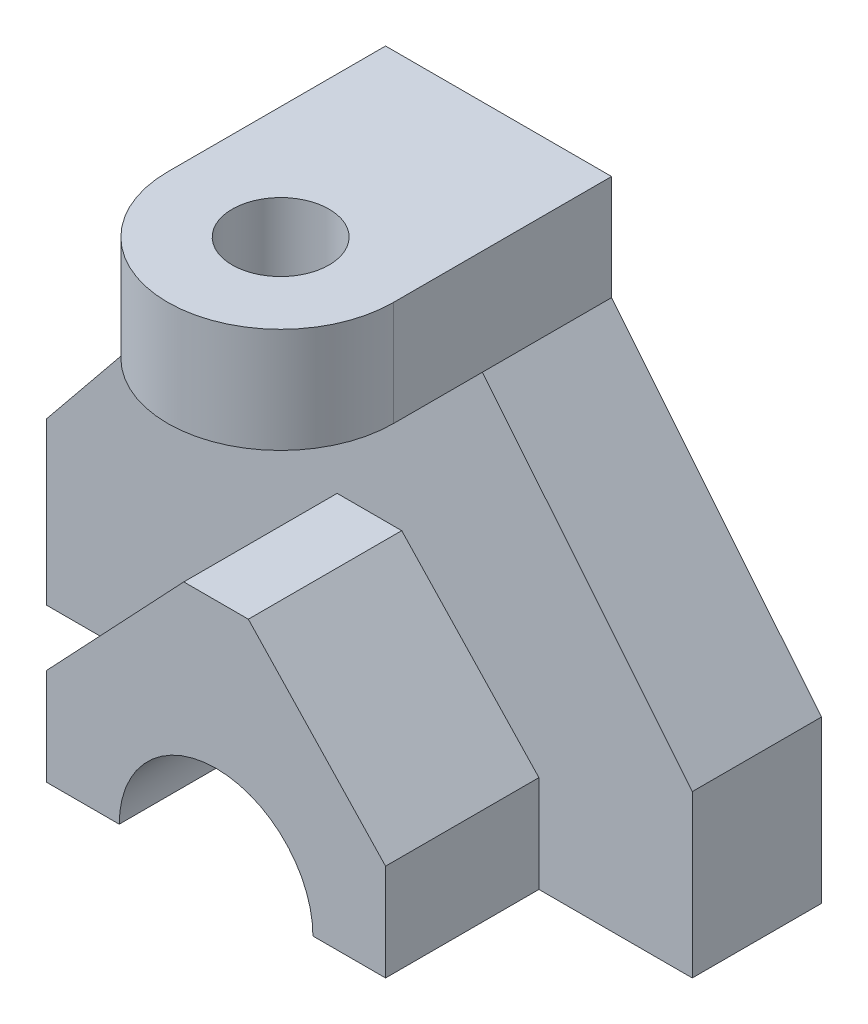
SolidWorks part; units mm, degrees
ref_plane "前视基准面" through (0, 0, 0) normal (0, 0, 1) x (1, 0, 0)
ref_plane "上视基准面" through (0, 0, 0) normal (0, 1, 0) x (1, 0, 0)
ref_plane "右视基准面" through (0, 0, 0) normal (1, 0, 0) x (0, 0, -1)
other "Configuration Table"
sketch "草图1" plane through (0, 0, 0) normal (0, 0, 1) x (1, 0, 0)
  line L0 (0, 0) -> (-40, 0)
  line L1 (0, 0) -> (0, 52)
  line L2 (-40, 0) -> (-40, 20)
  line L3 (0, 52) -> (-14, 52)
  line L4 (-14, 52) -> (-40, 20)
  dimension "D1" = 40
  dimension "D2" = 20
  dimension "D3" = 52
  dimension "D4" = 14
extrude "凸台-拉伸1" add sketch "草图1" along normal blind 16
mirror "镜向1" about plane through (0, 0, 16) normal (-1, 0, 0) of "凸台-拉伸1"
sketch "草图3" plane through (0, 52, 0) normal (0, 1, 0) x (1, 0, 0)
  line L0 (-14, 0) -> (-14, -27)
  line L1 (-14, 0) -> (14, 0)
  line L2 (14, 0) -> (14, -27)
  arc A0 (-14, -27) -> (14, -27) centre (0, -27) ccw
  dimension "D1" = 27
extrude "凸台-拉伸2" add sketch "草图3" along normal blind 13
sketch "草图4" plane through (0, 65, 0) normal (0, 1, 0) x (1, 0, 0)
  circle A0 centre (0, -27) radius 6
  dimension "D1" = 12
extrude "切除-拉伸1" cut sketch "草图4" against normal blind 13
sketch "草图5" plane through (0, 0, 16) normal (0, 0, 1) x (1, 0, 0)
  line L0 (0, 0) -> (-21, 0)
  line L1 (-40, 0) -> (40, 0) construction
  line L2 (-21, 0) -> (-21, 12)
  line L3 (-21, 12) -> (-4, 30)
  line L4 (0, 0) -> (0, 30)
  line L5 (0, 30) -> (-4, 30)
  point P5 (0, 0)
  point P11 (-7.7604, 28.9699)
  dimension "D1" = 21
  dimension "D2" = 12
  dimension "D3" = 30
  dimension "D4" = 4
extrude "凸台-拉伸3" add sketch "草图5" along normal blind 19
mirror "镜向2" about plane through (0, 0, 35) normal (-1, 0, 0) of "凸台-拉伸3"
sketch "草图6" plane through (0, 0, 35) normal (0, 0, 1) x (1, 0, 0)
  line L0 (-12, 0) -> (12, 0)
  arc A0 (12, 0) -> (-12, 0) centre (0, 0) ccw
  dimension "D1" = 12
extrude "切除-拉伸2" cut sketch "草图6" against normal blind 35
